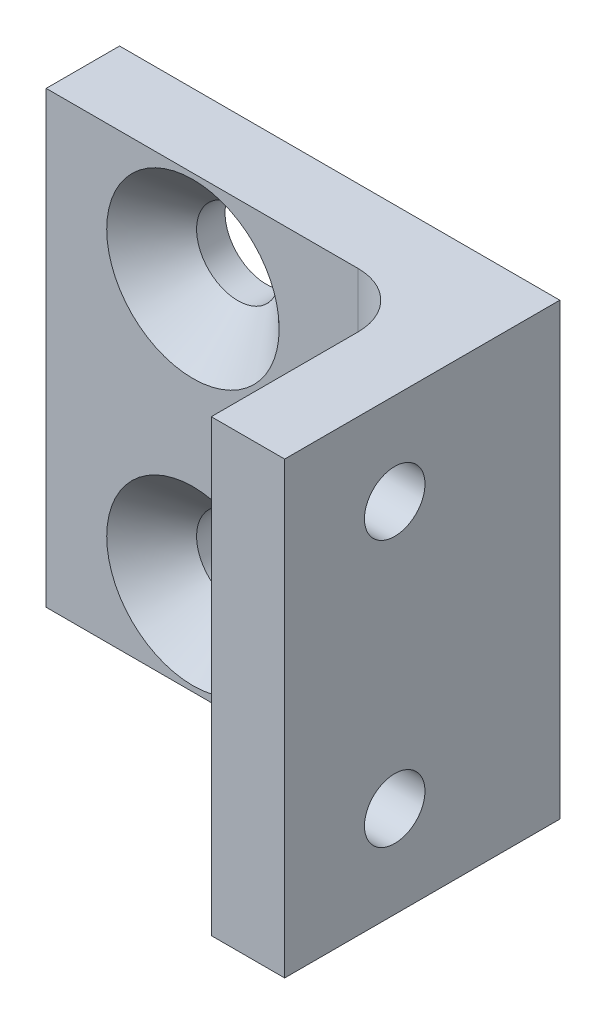
SolidWorks part; units mm, degrees
ref_plane "Front Plane" through (0, 0, 0) normal (0, 0, 1) x (1, 0, 0)
ref_plane "Top Plane" through (0, 0, 0) normal (0, 1, 0) x (1, 0, 0)
ref_plane "Right Plane" through (0, 0, 0) normal (1, 0, 0) x (0, 0, -1)
sketch "Sketch2" plane through (0, 0, 0) normal (0, 1, 0) x (1, 0, 0)
  line L0 (0, 0) -> (-24, 0)
  line L1 (-55, 0) -> (55, 0) construction
  line L2 (-24, 0) -> (-24, -4)
  line L3 (-24, -4) -> (-4, -4)
  line L4 (-4, -4) -> (-4, -15)
  line L5 (-4, -15) -> (0, -15)
  line L6 (0, -55) -> (0, 55) construction
  line L7 (0, -15) -> (0, 0)
  dimension "D1" = 24
  dimension "D2" = 4
  dimension "D3" = 4
  dimension "D4" = 15
extrude "Boss-Extrude1" add sketch "Sketch2" along normal blind 24.5
sketch "Sketch3" plane through (0, 0, 4) normal (0, 0, 1) x (1, 0, 0)
  line L0 (-24, 12.25) -> (9.0111, 12.25) construction
  line L1 (-24, 24.5) -> (-24, 0) construction
  line L2 (0, -12.4394) -> (0, 12.4394) construction
  point P4 (-16, 19.5)
  point P7 (-16, 5)
  point P9 (-14.6122, 12.9375)
  dimension "D1" = 16
  dimension "D2" = 7.25
sketch "Sketch4" plane through (-4, 0, 0) normal (-1, 0, 0) x (0, 0, 1)
  line L0 (15, 12.25) -> (-7.617, 12.25) construction
  line L1 (15, 24.5) -> (15, 0) construction
  line L2 (0, -13.2) -> (0, 13.2) construction
  point P4 (9, 19.5)
  point P7 (0, 0)
  point P8 (9, 5)
  dimension "D1" = 9
  dimension "D2" = 7.25
hole_wizard "CSK for M4 Flat Head Machine Screw1" positions "Sketch3" profile "Sketch5" countersink size "M4" standard "ANSI Metric" end condition through all
sketch "Sketch5" plane through (-16, 5, 4) normal (1, 0, 0) x (0, -1, 0)
  line L0 (0, 0) -> (0, 4)
  line L1 (0, 4) -> (2.25, 4)
  line L2 (2.25, 4) -> (2.25, 2.45)
  line L3 (2.25, 2.45) -> (4.7, 0)
  line L5 (4.7, 0) -> (0, 0)
  line L6 (-2.25, 2.45) -> (-4.7, 0) construction
  line L11 (0, -6.35) -> (0, 107.95) construction
  dimension "Thru Hole Dia." = 4.5
  dimension "Thru Hole Depth" = 4
  dimension "Near C'Sink Dia." = 9.4
  dimension "Near C'Sink Angle" = 90
hole_wizard "Tap Drill for M4x0.7 Tap1" positions "Sketch4" profile "Sketch6" hole size "M4x0.7" standard "ANSI Metric" end condition through all
sketch "Sketch6" plane through (-4, 5, 9) normal (0, 1, 0) x (0, 0, 1)
  line L0 (0, 0) -> (0, 4)
  line L1 (0, 4) -> (1.65, 4)
  line L2 (1.65, 4) -> (1.65, 0)
  line L5 (1.65, 0) -> (0, 0)
  line L11 (0, -6.35) -> (0, 107.95) construction
  dimension "Thru Hole Dia." = 3.3
  dimension "Thru Hole Depth" = 4
fillet "Fillet1" radius 3 1 edges at (-4, 12.25, 4)
